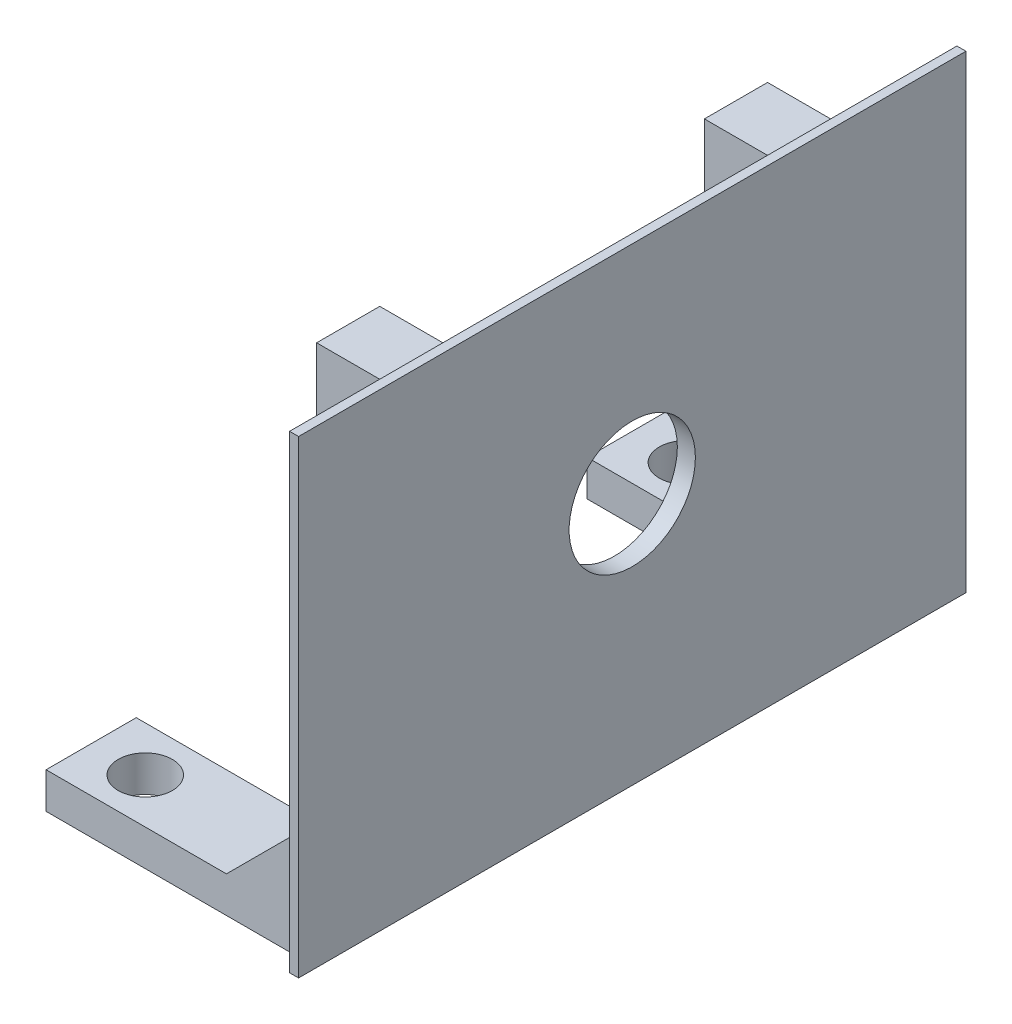
SolidWorks part; units mm, degrees
material "ABS"
ref_plane "Ebene vorne" through (0, 0, 0) normal (0, 0, 1) x (1, 0, 0)
ref_plane "Ebene oben" through (0, 0, 0) normal (0, 1, 0) x (1, 0, 0)
ref_plane "Ebene rechts" through (0, 0, 0) normal (1, 0, 0) x (0, 0, -1)
sketch "Skizze2" plane through (0, 0, 0) normal (1, 0, 0) x (0, 0, -1)
  line L0 (0, 0) -> (0, 47.3055) construction
  line L2 (-12.5, 25) -> (12.5, 25)
  line L3 (-12.5, 25) -> (-12.5, 0)
  line L4 (-12.5, 0) -> (12.5, 0)
  line L5 (12.5, 25) -> (12.5, 0)
  line L6 (-12.5, 25) -> (12.5, 0) construction
  line L7 (-12.5, 0) -> (12.5, 25) construction
  line L8 (-17.5, -1) -> (17.5, -1)
  line L9 (-17.5, -1) -> (-17.5, 0)
  line L10 (-17.5, 0) -> (17.5, 0)
  line L11 (17.5, -1) -> (17.5, 0)
  line L12 (-17.5, -1) -> (17.5, 0) construction
  line L13 (-17.5, 0) -> (17.5, -1) construction
  circle A0 centre (0, 13) radius 3.5
  point P3 (0, 12.5)
  point P8 (0, -0.5)
  point P9 (0, 13)
  dimension "D1" = 7
  dimension "D2" = 13
  dimension "D3" = 25
  dimension "D4" = 1
  dimension "D5" = 25
  dimension "D6" = 5
extrude "Front Face" add sketch "Skizze2" along normal blind 1 contours L5 L2 L3 L4 A0 | L8 L11 L10 L4 L9
sketch "Skizze3" plane through (0, 0, 0) normal (-1, 0, 0) x (0, 0, 1)
  line L0 (17.5, -1) -> (-17.5, -1) construction
  line L1 (-12.5, 25) -> (-9, 25)
  line L2 (-12.5, 25) -> (-12.5, -1)
  line L3 (-12.5, -1) -> (-9, -1)
  line L4 (-9, 25) -> (-9, -1)
  line L5 (12.5, 25) -> (9, 25)
  line L6 (12.5, 25) -> (12.5, -1)
  line L7 (12.5, -1) -> (9, -1)
  line L8 (9, 25) -> (9, -1)
  line L9 (0, 0) -> (0, 32.5232) construction
  line L10 (-12.5, 0) -> (-17.5, 0) construction
  line L11 (-10.75, 25) -> (-10.75, -1) construction
  line L13 (12.5, 25) -> (-12.5, 25) construction
  line L14 (-12.5, 25) -> (-12.5, 0) construction
  line L15 (12.5, 25) -> (12.5, 0) construction
  circle A0 centre (-10.75, 14) radius 0.75
  circle A1 centre (-10.75, 1.5) radius 0.75
  circle A2 centre (10.75, 1.5) radius 0.75
  circle A3 centre (10.75, 14) radius 0.75
  dimension "D2" = 1.5
  dimension "D1" = 3.5
  dimension "D3" = 1.5
  dimension "D4" = 14
extrude "Camera Spacer" add sketch "Skizze3" along normal blind 4
ref_plane "Ebene1" through (0, 0, -17.5) normal (0, 1, 0) x (1, 0, 0)
sketch "Skizze6" plane through (0, 0, 0) normal (-1, 0, 0) x (0, 0, 1)
  line L1 (-12.5, -1) -> (-17.5, -1)
  line L2 (-12.5, -1) -> (-12.5, 1)
  line L3 (-12.5, 1) -> (-17.5, 1)
  line L4 (-17.5, -1) -> (-17.5, 1)
  line L5 (-17.5, -1) -> (-17.5, 0) construction
  line L6 (17.5, -1) -> (17.5, 0) construction
  line L7 (17.5, 1) -> (12.5, 1)
  line L8 (17.5, 1) -> (17.5, -1)
  line L9 (17.5, -1) -> (12.5, -1)
  line L10 (12.5, 1) -> (12.5, -1)
  dimension "D1" = 2
extrude "Floor Plate" add sketch "Skizze6" along normal blind 14 and the other way offset from surface (0.5 mm away) 0.5 other way up to face at (0, 12, 0)
sketch "Skizze7" plane through (1, 0, 0) normal (1, 0, 0) x (0, 0, -1)
  line L0 (-9, -1) -> (9, -1) construction
  line L1 (12.5, 25) -> (18.5, 25)
  line L2 (12.5, 25) -> (12.5, -1)
  line L3 (12.5, -1) -> (18.5, -1)
  line L4 (18.5, 25) -> (18.5, -1)
  line L5 (-12.5, 25) -> (-18.5, 25)
  line L6 (-12.5, 25) -> (-12.5, -1)
  line L7 (-12.5, -1) -> (-18.5, -1)
  line L8 (-18.5, 25) -> (-18.5, -1)
  line L9 (0, 0) -> (0, 25) construction
  line L10 (-9, 25) -> (9, 25) construction
  dimension "D1" = 37
extrude "Side Covers" add sketch "Skizze7" against normal blind 0.5
sketch "Skizze8" plane through (-4, 0, 0) normal (-1, 0, 0) x (0, 0, 1)
  line L0 (12.5, 1) -> (12.5, 25) construction
  line L1 (-12.5, 25) -> (12.5, 25)
  line L2 (-12.5, 25) -> (-12.5, 24)
  line L3 (-12.5, 24) -> (12.5, 24)
  line L4 (12.5, 25) -> (12.5, 24)
  dimension "D1" = 1
extrude "Top Cover" cut sketch "Skizze8" against normal up to surface (4.5 mm away) up to face at (0.5, 8.3333, -16.1667)
chamfer "Fase1" distance 4.5 angle 45 2 edges at (0.5, 1, 15) (0.5, 1, -15)
hole_wizard "Ø3.0 (3) Durchmesser Bohrung1" positions "Skizze10" profile "Skizze11" hole size "Ø3.0" standard "ISO" end condition through all
sketch "Skizze10" plane through (0, 1, 0) normal (0, 1, 0) x (1, 0, 0)
  line L0 (0, 0) -> (-14.7862, 0) construction
  line L1 (-14, 12.5) -> (-14, 17.5) construction
  point P0 (-11, 15)
  point P2 (-11, -15)
  dimension "D1" = 30
  dimension "D2" = 3
sketch "Skizze11" plane through (-11, 1, -15) normal (1, 0, 0) x (0, 0, 1)
  line L0 (0, 0) -> (0, 2)
  line L1 (0, 2) -> (1.5, 2)
  line L2 (1.5, 2) -> (1.5, 0)
  line L5 (1.5, 0) -> (0, 0)
  line L11 (0, -6.35) -> (0, 107.95) construction
  dimension "Bohrerdurchmesser" = 3
  dimension "Bohrungstiefe" = 2
